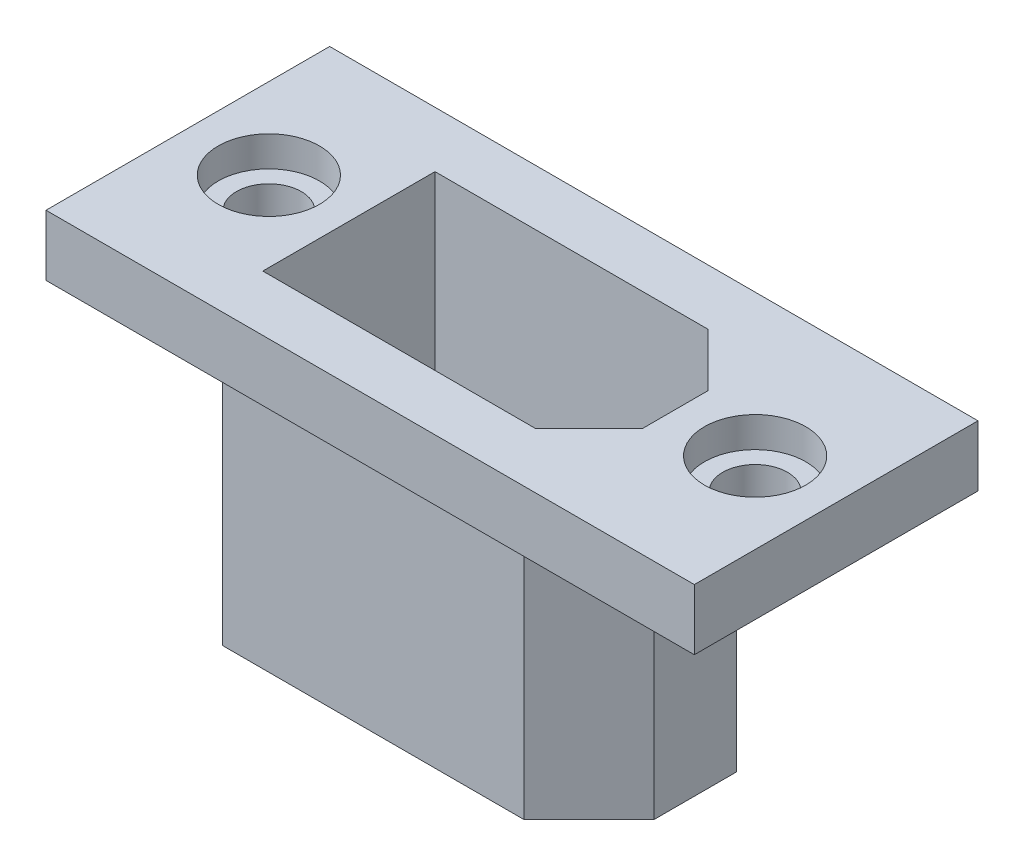
SolidWorks part; units mm, degrees
ref_plane "Front Plane" through (0, 0, 0) normal (0, 0, 1) x (1, 0, 0)
ref_plane "Top Plane" through (0, 0, 0) normal (0, 1, 0) x (1, 0, 0)
ref_plane "Right Plane" through (0, 0, 0) normal (1, 0, 0) x (0, 0, -1)
sketch "Sketch1" plane through (0, 0, 0) normal (0, 1, 0) x (1, 0, 0)
  line L1 (-16, 7) -> (16, 7)
  line L2 (-16, 7) -> (-16, -7)
  line L3 (-16, -7) -> (16, -7)
  line L4 (16, 7) -> (16, -7)
  line L5 (-16, 7) -> (16, -7) construction
  line L6 (-16, -7) -> (16, 7) construction
  point P0 (0, 0)
  dimension "D1" = 32
  dimension "D2" = 14
extrude "Boss-Extrude1" add sketch "Sketch1" along normal blind 3
sketch "Sketch2" plane through (0, 3, 0) normal (0, 1, 0) x (1, 0, 0)
  line L0 (-7.75, -3.95) -> (-7.75, 3.95) construction
  line L1 (-7.75, 3.95) -> (5.3, 3.95) construction
  line L2 (5.3, 3.95) -> (7.75, 1.5) construction
  line L3 (7.75, 1.5) -> (7.75, -1.5) construction
  line L4 (7.75, -1.5) -> (5.3, -3.95) construction
  line L5 (5.3, -3.95) -> (-7.75, -3.95) construction
  line L6 (5.4243, -4.25) -> (-8.05, -4.25)
  line L7 (-8.05, -4.25) -> (-8.05, 4.25)
  line L8 (-8.05, 4.25) -> (5.4243, 4.25)
  line L9 (5.4243, 4.25) -> (8.05, 1.6243)
  line L10 (8.05, 1.6243) -> (8.05, -1.6243)
  line L11 (8.05, -1.6243) -> (5.4243, -4.25)
  dimension "D1" = 0.3
extrude "Cut-Extrude1" cut sketch "Sketch2" against normal blind 3
sketch "Sketch3" plane through (0, 3, 0) normal (0, 1, 0) x (1, 0, 0)
  line L0 (-8.05, -4.25) -> (-8.05, 4.25)
  line L1 (-8.05, 4.25) -> (5.4243, 4.25)
  line L2 (5.4243, 4.25) -> (8.05, 1.6243)
  line L3 (8.05, 1.6243) -> (8.05, -1.6243)
  line L4 (8.05, -1.6243) -> (5.4243, -4.25)
  line L5 (5.4243, -4.25) -> (-8.05, -4.25)
  line L6 (5.8385, -5.25) -> (-9.05, -5.25)
  line L7 (-9.05, -5.25) -> (-9.05, 5.25)
  line L8 (-9.05, 5.25) -> (5.8385, 5.25)
  line L9 (5.8385, 5.25) -> (9.05, 2.0385)
  line L10 (9.05, 2.0385) -> (9.05, -2.0385)
  line L11 (9.05, -2.0385) -> (5.8385, -5.25)
  dimension "D1" = 1
extrude "Boss-Extrude2" add sketch "Sketch3" against normal blind 16
sketch "Sketch4" plane through (0, 3, 0) normal (0, 1, 0) x (1, 0, 0)
  line L0 (0, 0) -> (0, -2.8495) construction
  circle A0 centre (-12, 0) radius 1.6
  circle A1 centre (12, 0) radius 1.6
  dimension "D1" = 24
extrude "Cut-Extrude2" cut sketch "Sketch4" against normal blind 3
sketch "Sketch5" plane through (0, 3, 0) normal (0, 1, 0) x (1, 0, 0)
  circle A0 centre (-12, 0) radius 2.5
  circle A1 centre (12, 0) radius 2.5
extrude "Cut-Extrude3" cut sketch "Sketch5" against normal blind 1.5
